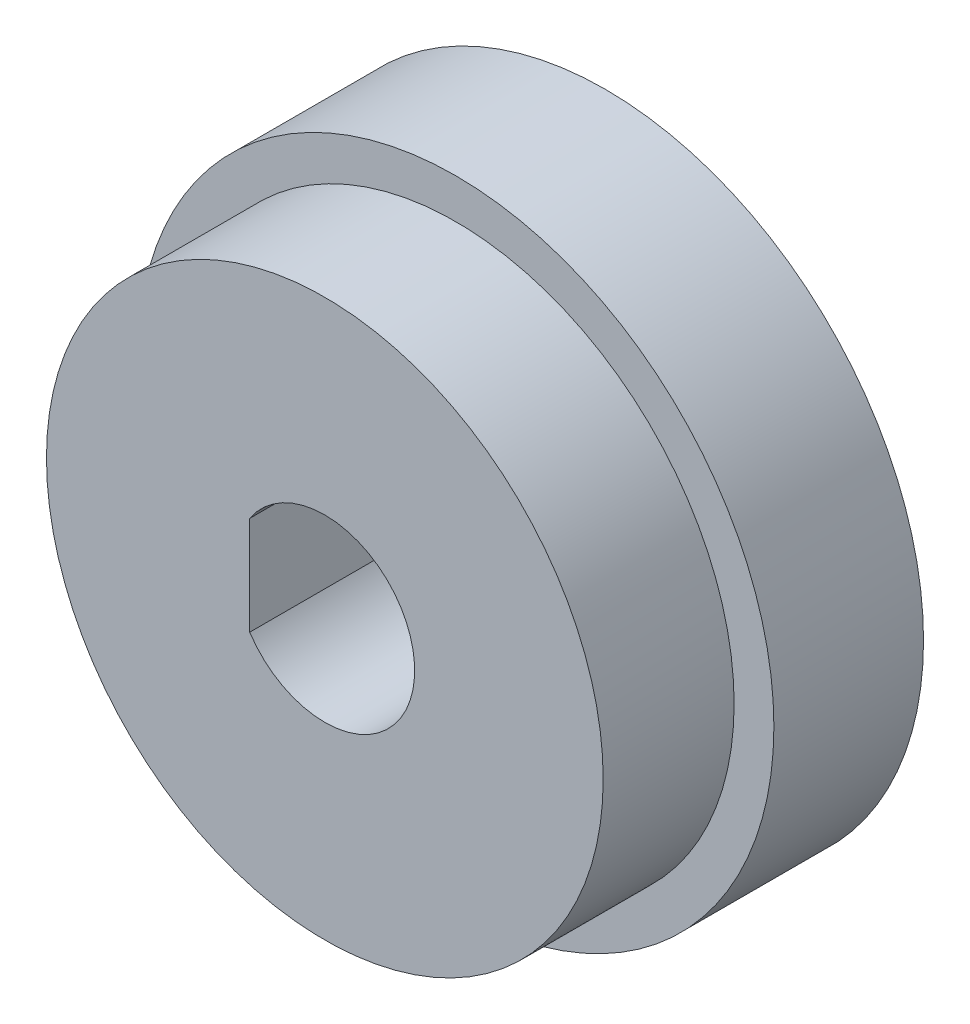
SolidWorks part; units mm, degrees
ref_plane "Front Plane" through (0, 0, 0) normal (0, 0, 1) x (1, 0, 0)
ref_plane "Top Plane" through (0, 0, 0) normal (0, 1, 0) x (1, 0, 0)
ref_plane "Right Plane" through (0, 0, 0) normal (1, 0, 0) x (0, 0, -1)
sketch "Sketch1" plane through (0, 0, 0) normal (0, 0, 1) x (1, 0, 0)
  circle A0 centre (0, 0) radius 10.8
  dimension "D1" = 21.6
extrude "Boss-Extrude1" add sketch "Sketch1" along normal blind 5.08
sketch "Sketch2" plane through (0, 0, 5.08) normal (0, 0, 1) x (1, 0, 0)
  circle A0 centre (0, 0) radius 9.45
  dimension "D1" = 18.9
extrude "Boss-Extrude2" add sketch "Sketch2" along normal blind 4.445
sketch "Sketch3" plane through (0, 0, 9.525) normal (0, 0, 1) x (1, 0, 0)
  line L1 (-2.55, 0) -> (-2.55, 1.6733)
  line L3 (-2.55, 0) -> (-2.55, -1.6733)
  arc A2 (-2.55, -1.6733) -> (-2.55, 1.6733) centre (0, 0) ccw
  point P1 (3.05, 0)
  dimension "D1" = 6.1
  dimension "D2" = 5.6
extrude "Cut-Extrude1" cut sketch "Sketch3" against normal through all
